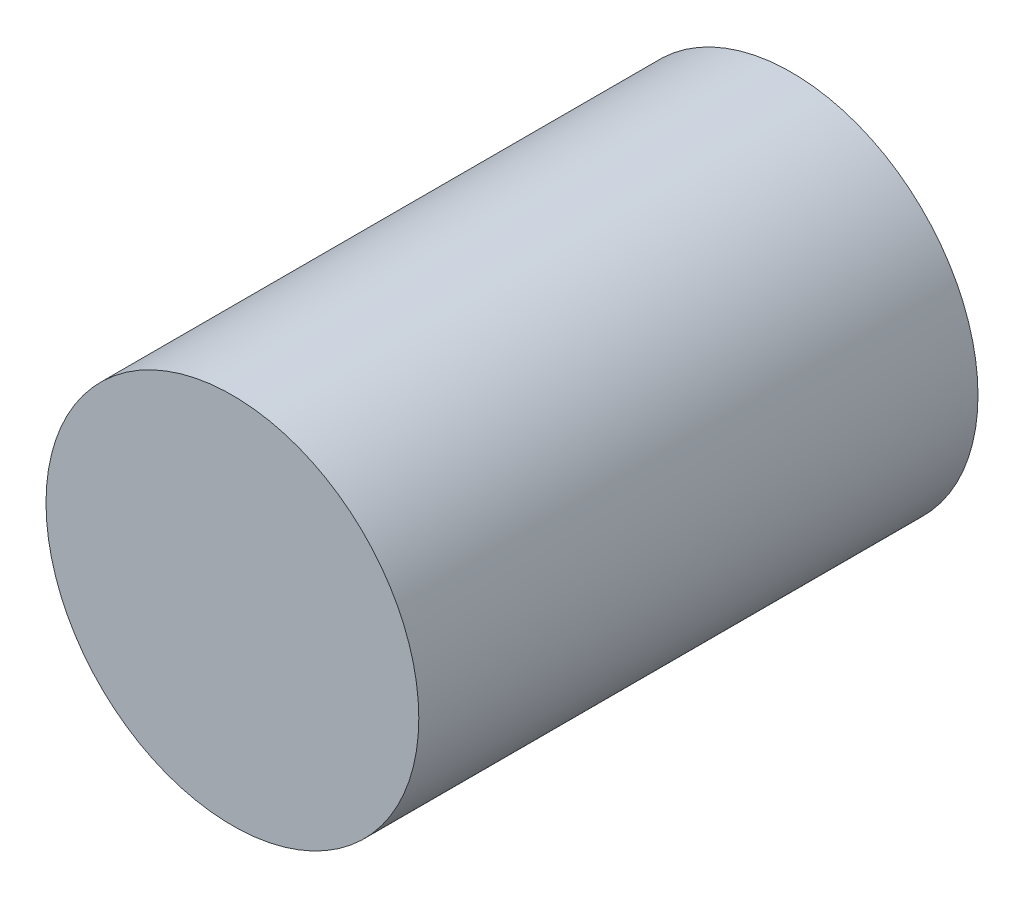
SolidWorks part; units mm, degrees
material "Paracadute"
ref_plane "Piano frontale" through (0, 0, 0) normal (0, 0, 1) x (1, 0, 0)
ref_plane "Piano superiore" through (0, 0, 0) normal (0, 1, 0) x (1, 0, 0)
ref_plane "Piano destro" through (0, 0, 0) normal (1, 0, 0) x (0, 0, -1)
sketch "Schizzo1" plane through (0, 0, 0) normal (0, 0, 1) x (1, 0, 0)
  circle A0 centre (0, 0) radius 50
  dimension "D1" = 100
extrude "Estrusione-Estrusione1" add sketch "Schizzo1" along normal blind 150
